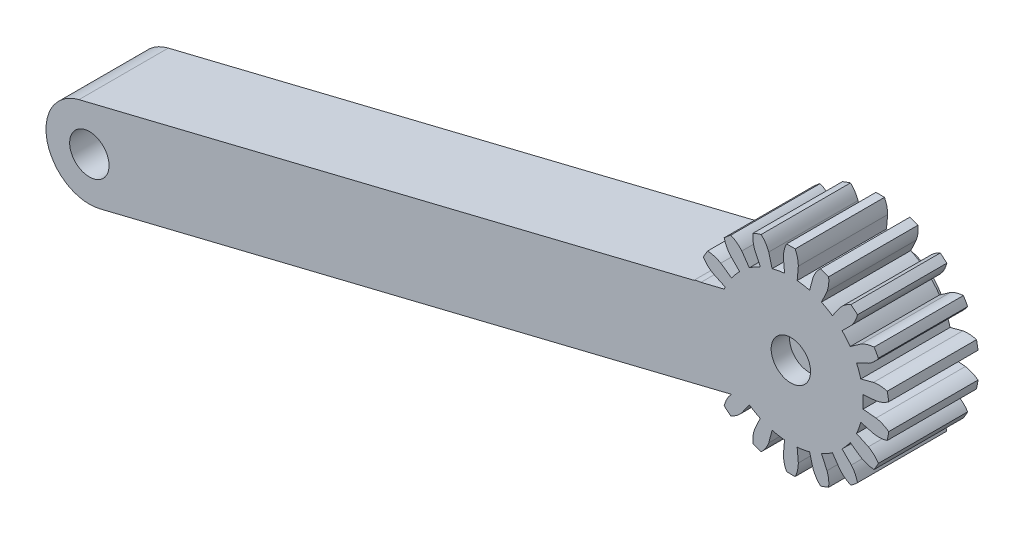
SolidWorks part; units mm, degrees
ref_plane "Front Plane" through (0, 0, 0) normal (0, 0, 1) x (1, 0, 0)
ref_plane "Top Plane" through (0, 0, 0) normal (0, 1, 0) x (1, 0, 0)
ref_plane "Right Plane" through (0, 0, 0) normal (1, 0, 0) x (0, 0, -1)
sketch "Sketch2" plane through (0, 0, 0) normal (0, 0, 1) x (1, 0, 0)
  line L0 (-8.763, -27.305) -> (0.6332, -25.6482) construction
  line L1 (-8.763, -27.305) -> (0.552, -25.2399) construction
  line L2 (-8.763, -27.305) -> (0.4531, -24.8356) construction
  line L3 (-8.763, -27.305) -> (0.2028, -24.0417) construction
  line L7 (0.7689, -27.7321) -> (0.7782, -27.305)
  line L10 (0, -5.08) -> (-0.3761, -22.1462) construction
  line L11 (-0.3761, -22.1462) -> (-0.7314, -38.2679) construction
  line L12 (-32.5853, -5.08) -> (32.5853, -5.08) construction
  line L13 (-8.763, -27.305) -> (-2.184, -24.9105)
  line L14 (-2.0004, -25.493) -> (-0.7737, -25.1643)
  line L15 (-1.7885, -26.6948) -> (-0.5233, -26.5841)
  line L16 (-8.763, -27.305) -> (-1.7618, -27.305)
  line L17 (-8.763, -27.305) -> (-2.4532, -27.305) construction
  circle A1 centre (-8.763, -27.305) radius 8.2712 construction
  circle A2 centre (-8.763, -27.305) radius 9.5412 construction
  circle A7 centre (-8.763, -27.305) radius 7.0012 construction
  arc A8 (-2.184, -24.9105) -> (-2.0004, -25.493) centre (-8.763, -27.305) cw
  arc A9 (0.552, -25.2399) -> (0.6965, -26.0596) centre (-8.763, -27.305) cw
  arc A10 (-0.7737, -25.1643) -> (0.552, -25.2399) centre (-0.2654, -27.9117) cw
  arc A11 (-0.5233, -26.5841) -> (0.6965, -26.0596) centre (-0.9854, -23.8286) ccw
  arc A12 (-1.7618, -27.305) -> (-1.7885, -26.6948) centre (-8.763, -27.305) ccw
  dimension "D1" = 1.27
  dimension "D2" = 1.27
  dimension "D6" = 2.794
  dimension "D3" = 2.5
  dimension "D4" = 5
  dimension "D5" = 10
  dimension "D7" = 10
extrude "Boss-Extrude2" add sketch "Sketch2" along normal up to surface (12.7 mm away)
pattern_circular "CirPattern1" count 18 every 20 about axis through (-8.763, -27.305, 0) along (0, 0, 1) of "Boss-Extrude2"
sketch "Sketch4" plane through (0, 0, 0) normal (0, 0, -1) x (-1, 0, 0)
  line L0 (10.2489, -29.2862) -> (10.2489, -25.3238)
  line L1 (7.2771, -25.3238) -> (7.2771, -29.2862)
  arc A0 (10.2489, -29.2862) -> (7.2771, -29.2862) centre (8.763, -27.305) cw
  arc A1 (10.2489, -25.3238) -> (7.2771, -25.3238) centre (8.763, -27.305) ccw
extrude "Cut-Extrude1" cut sketch "Sketch4" against normal blind 7.62
ref_plane "Plane1" through (-8.763, 0, 0) normal (-1, 0, 0) x (0, 0, 1)
sketch "Sketch5" plane through (-8.763, 0, 0) normal (-1, 0, 0) x (0, 0, 1)
  line L0 (12.7, -31.7106) -> (0, -31.7106) construction
  line L1 (0, -37.5279) -> (2.032, -37.5279)
  line L2 (0, -37.5279) -> (0, -31.7106)
  line L3 (0, -31.7106) -> (2.032, -31.7106)
  line L4 (2.032, -37.5279) -> (2.032, -31.7106)
  line L5 (6.35, -36.8371) -> (6.35, -31.1044) construction
  line L6 (12.7, -36.8371) -> (0, -36.8371) construction
  line L7 (12.7, -37.5279) -> (10.668, -37.5279)
  line L8 (12.7, -37.5279) -> (12.7, -31.7106)
  line L9 (12.7, -31.7106) -> (10.668, -31.7106)
  line L10 (10.668, -37.5279) -> (10.668, -31.7106)
  line L11 (-1.27, -27.305) -> (15.6856, -27.305) construction
  line L12 (-1.27, -29.2862) -> (-1.27, -25.3238) construction
  dimension "D1" = 2.032
  dimension "D2" = 5.8173
  dimension "D3" = 4.4056
ref_axis "Axis1" through (-8.763, -27.305, 7.62) along (0, 0, -1)
revolve "Cut-Revolve1" cut sketch "Sketch5" angle 360 about axis through (-8.763, -27.305, 7.62) along (0, 0, -1)
sketch "Sketch6" plane through (0, 0, 12.7) normal (0, 0, 1) x (1, 0, 0)
  circle A0 centre (-8.763, -27.305) radius 1.905
  dimension "D1" = 3.81
extrude "Cut-Extrude2" cut sketch "Sketch6" against normal blind 3.81
ref_plane "Plane2" through (0, 0, 6.35) normal (0, 0, -1) x (-1, 0, 0)
sketch "Sketch7" plane through (0, 0, 6.35) normal (0, 0, -1) x (-1, 0, 0)
  line L0 (37.9337, -27.305) -> (-32.4388, -27.305) construction
  line L1 (-8.89, -27.432) -> (-76.6611, -44.3466) construction
  line L2 (8.763, -27.305) -> (53.7214, -38.3478) construction
  line L3 (8.763, -27.305) -> (76.5967, -43.9666) construction
  line L4 (11.4545, -23.6505) -> (77.5964, -39.8965)
  line L5 (9.4551, -31.7906) -> (75.597, -48.0366)
  arc A1 (75.597, -48.0366) -> (77.5964, -39.8965) centre (76.5967, -43.9666) ccw
  circle A2 centre (76.5967, -43.9666) radius 1.905
  arc A3 (11.4545, -23.6505) -> (9.4551, -31.7906) centre (8.8151, -27.3178) cw
  point P8 (42.6799, -35.6358)
  dimension "D4" = 4.191
  dimension "D5" = 3.81
  dimension "D1" = 69.85
  dimension "D2" = 13.8
  dimension "D3" = 69.85
extrude "Boss-Extrude3" add sketch "Sketch7" along normal mid plane 8.636
sketch "Sketch8" plane through (0, 0, 10.668) normal (0, 0, 1) x (1, 0, 0)
  circle A0 centre (-8.763, -27.305) radius 4.4056
extrude "Cut-Extrude3" cut sketch "Sketch8" along normal up to surface (2.032 mm away) up to face at (-6.858, -27.305, 12.7)
